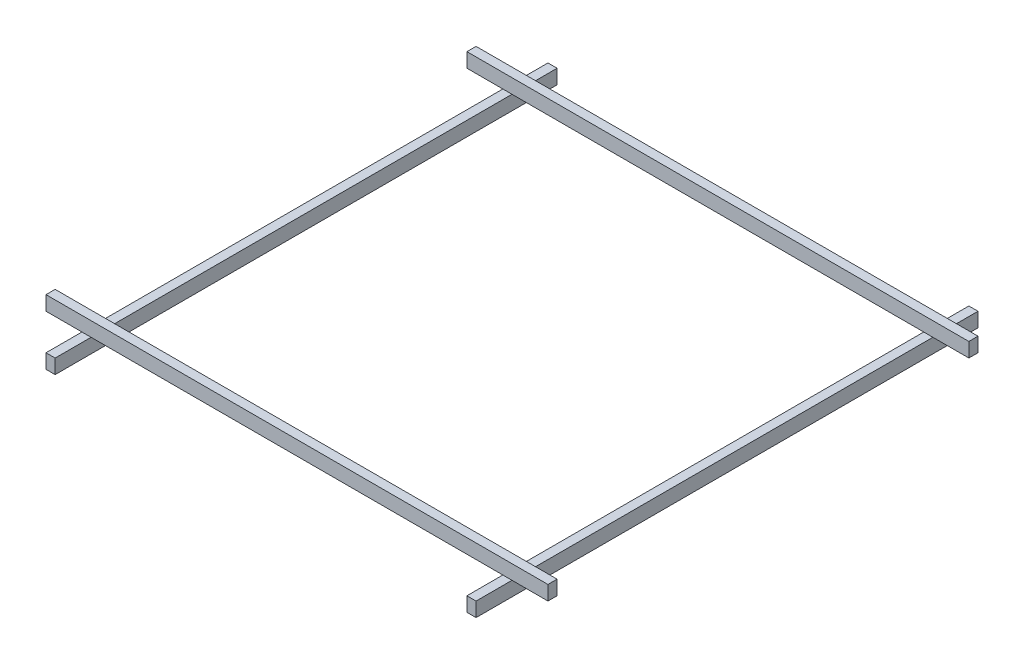
SolidWorks part; units mm, degrees
material "Doug Fir"
ref_plane "Front Plane" through (0, 0, 0) normal (0, 0, 1) x (1, 0, 0)
ref_plane "Top Plane" through (0, 0, 0) normal (0, 1, 0) x (1, 0, 0)
ref_plane "Right Plane" through (0, 0, 0) normal (1, 0, 0) x (0, 0, -1)
sketch "Lower Level" plane through (0, 0, 0) normal (0, 1, 0) x (1, 0, 0)
  line L0 (88.9, 0) -> (88.9, 4876.8)
  line L1 (4178.3, 0) -> (4178.3, 4876.8)
  line L2 (88.9, 2438.4) -> (4178.3, 2438.4) construction
  point P7 (2133.6, 2438.4)
  dimension "D1" = 4876.8
  dimension "D2" = 2044.7
ref_plane "Plane2" through (0, 139.7, 0) normal (0, 1, 0) x (1, 0, 0)
sketch "Sketch12" plane through (0, 139.7, 0) normal (0, 1, 0) x (1, 0, 0)
  line L0 (-304.8, 4483.1) -> (4572, 4483.1)
  line L1 (4572, 393.7) -> (-304.8, 393.7)
  line L2 (2133.6, 4483.1) -> (2133.6, 393.7) construction
  point P0 (2133.6, 2438.4)
  point P6 (2133.6, 393.7)
  point P7 (2133.6, 4483.1)
  point P10 (2133.6, 2438.4)
  dimension "D1" = 4876.8
  dimension "D2" = 2044.7
other "Profiles 4X6(1)"
ref_plane "Plane1" through (88.9, 0, 0) normal (0, 0, -1) x (-1, 0, 0)
sketch "Sketch1" plane through (88.9, 0, 0) normal (0, 0, -1) x (-1, 0, 0)
  line L1 (-44.45, 69.85) -> (44.45, 69.85)
  line L2 (-44.45, 69.85) -> (-44.45, -69.85)
  line L3 (-44.45, -69.85) -> (44.45, -69.85)
  line L4 (44.45, 69.85) -> (44.45, -69.85)
  line L5 (-44.45, 69.85) -> (44.45, -69.85) construction
  line L6 (-44.45, -69.85) -> (44.45, 69.85) construction
  point P0 (0, 0)
  point P6 (0, 69.85)
  point P7 (0, -69.85)
  point P8 (44.45, 0)
  point P9 (-44.45, 0)
  point P10 (0, 0)
  dimension "D1" = 88.9
  dimension "D2" = 139.7
sketch3d "3DSketch2"
  line L0 (2133.6, 139.7, -2438.4) -> (2133.6, 0, -2438.4)
  line L1 (88.9, 0, -2438.4) -> (4178.3, 0, -2438.4) construction
equation "\"Width\" = 80.5"
equation "\"Length\"=192"
equation "\"D1@Lower Level\"=\"Length\""
equation "\"D2@Lower Level\"=\"Width\""
equation "\"D1@Sketch12\"=\"Length\""
equation "\"D2@Sketch12\"=\"Width\""
